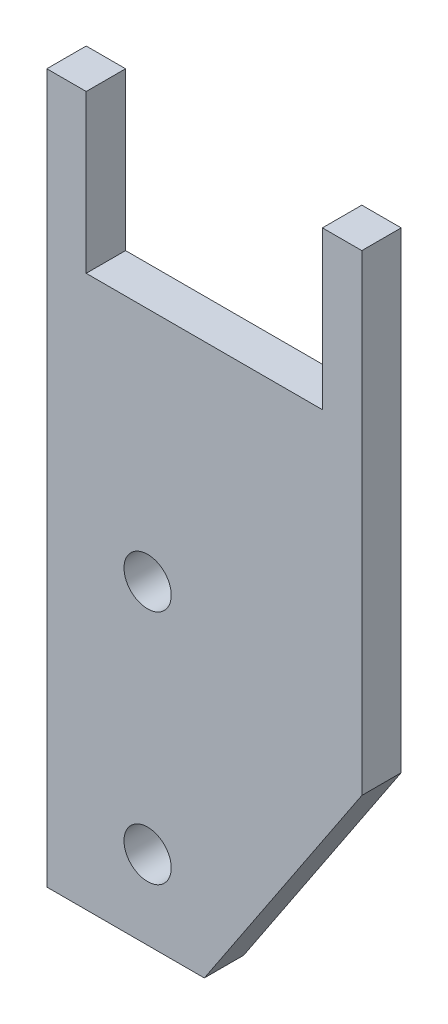
SolidWorks part; units mm, degrees
ref_plane "Front Plane" through (0, 0, 0) normal (0, 0, 1) x (1, 0, 0)
ref_plane "Top Plane" through (0, 0, 0) normal (0, 1, 0) x (1, 0, 0)
ref_plane "Right Plane" through (0, 0, 0) normal (1, 0, 0) x (0, 0, -1)
sketch "Sketch1" plane through (0, 0, 0) normal (0, 0, 1) x (1, 0, 0)
  line L0 (0, 0) -> (0, 25.4)
  line L1 (0, 25.4) -> (-6.35, 25.4)
  line L2 (-6.35, 25.4) -> (-6.35, -88.9)
  line L3 (0, 0) -> (38.1, 0)
  line L4 (38.1, 0) -> (38.1, 25.4)
  line L5 (38.1, 25.4) -> (44.45, 25.4)
  line L6 (44.45, 25.4) -> (44.45, 0.0964)
  line L7 (44.45, 0.0964) -> (44.45, -50.7036)
  line L8 (44.45, -50.7036) -> (19.05, -88.9)
  line L9 (19.05, -88.9) -> (-6.35, -88.9)
  circle A0 centre (9.906, -38.1) radius 3.81
  circle A1 centre (9.906, -76.2) radius 3.81
  dimension "D9" = 7.62
  dimension "D11" = 7.62
  dimension "D1" = 114.3
  dimension "D2" = 6.35
  dimension "D3" = 38.1
  dimension "D4" = 25.4
  dimension "D5" = 25.4
  dimension "D6" = 6.35
  dimension "D7" = 25.4
  dimension "D8" = 50.8
  dimension "D10" = 38.1
  dimension "D12" = 38.1
  dimension "D13" = 12.7
  dimension "D14" = 9.906
extrude "Boss-Extrude1" add sketch "Sketch1" along normal blind 6.35
